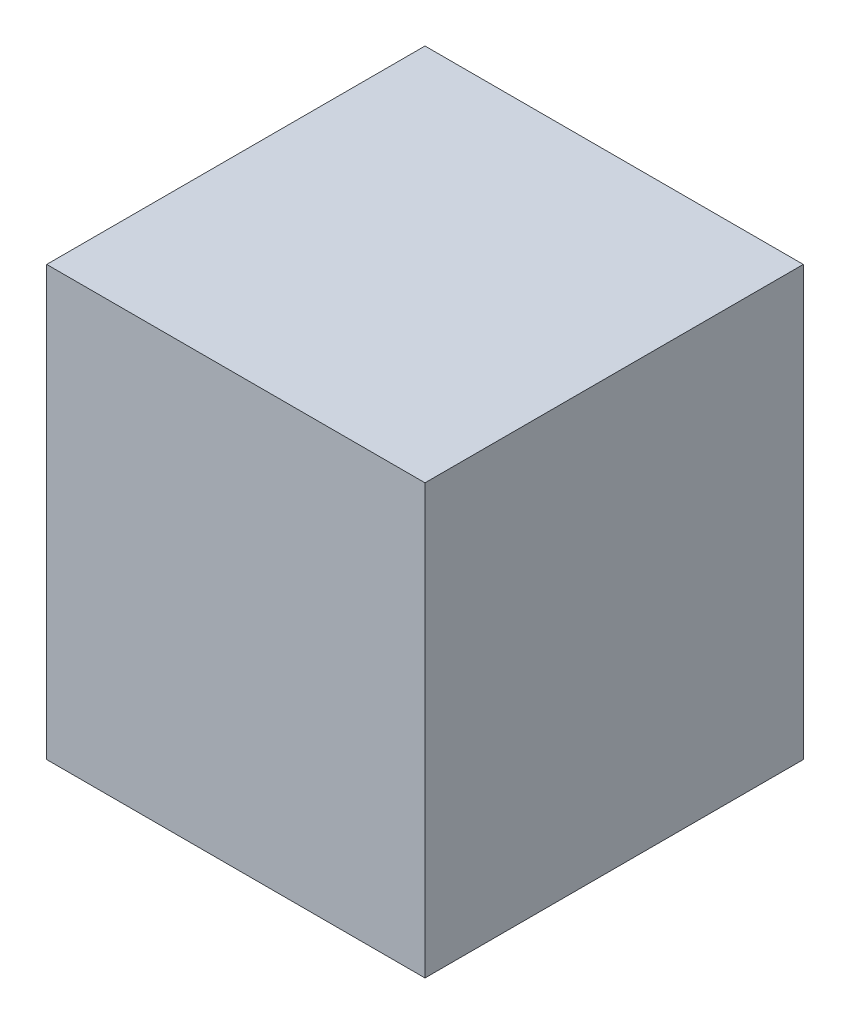
SolidWorks part; units mm, degrees
ref_plane "前视基准面" through (0, 0, 0) normal (0, 0, 1) x (1, 0, 0)
ref_plane "上视基准面" through (0, 0, 0) normal (0, 1, 0) x (1, 0, 0)
ref_plane "右视基准面" through (0, 0, 0) normal (1, 0, 0) x (0, 0, -1)
other "Configuration Table"
sketch "草图1" plane through (0, 0, 0) normal (0, 1, 0) x (1, 0, 0)
  line L1 (-2.5, -2.5) -> (2.5, -2.5)
  line L2 (-2.5, -2.5) -> (-2.5, 2.5)
  line L3 (-2.5, 2.5) -> (2.5, 2.5)
  line L4 (2.5, -2.5) -> (2.5, 2.5)
  line L5 (-2.5, -2.5) -> (2.5, 2.5) construction
  line L6 (-2.5, 2.5) -> (2.5, -2.5) construction
  point P0 (0, 0)
  dimension "D1" = 5
  dimension "D2" = 5
extrude "凸台-拉伸1" add sketch "草图1" along normal mid plane 5.668
